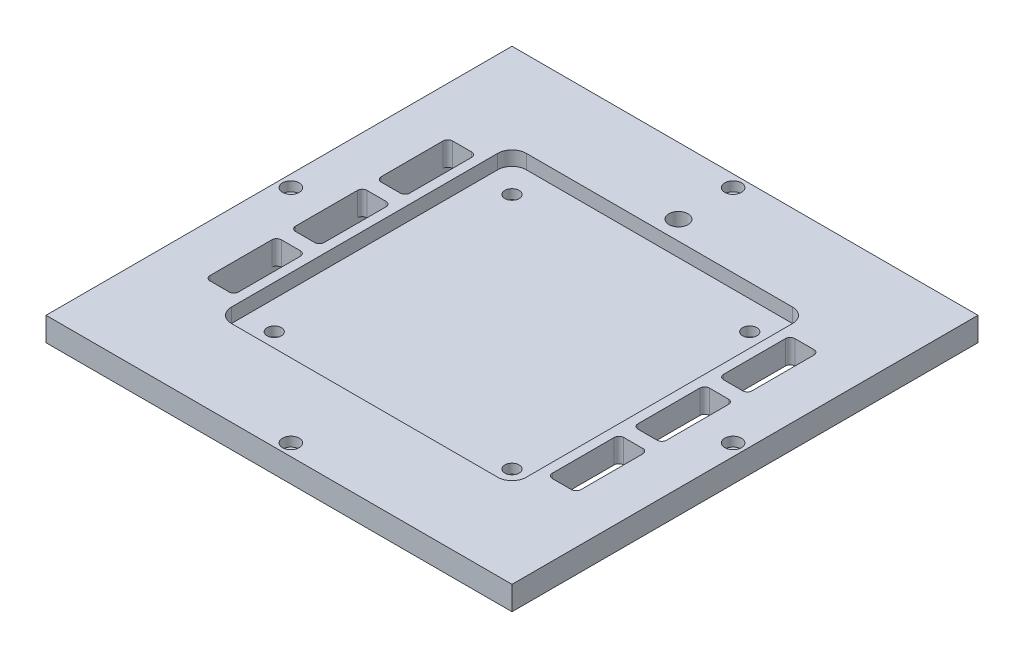
SolidWorks part; units mm, degrees
ref_plane "Front Plane" through (0, 0, 0) normal (0, 0, 1) x (1, 0, 0)
ref_plane "Top Plane" through (0, 0, 0) normal (0, 1, 0) x (1, 0, 0)
ref_plane "Right Plane" through (0, 0, 0) normal (1, 0, 0) x (0, 0, -1)
sketch "Sketch1" plane through (0, 0, 0) normal (0, 1, 0) x (1, 0, 0)
  line L1 (-49, 49) -> (49, 49)
  line L2 (-49, 49) -> (-49, -49)
  line L3 (-49, -49) -> (49, -49)
  line L4 (49, 49) -> (49, -49)
  line L5 (-49, 49) -> (49, -49) construction
  line L6 (-49, -49) -> (49, 49) construction
  point P0 (0, 0)
  dimension "D1" = 98
  dimension "D2" = 98
extrude "Boss-Extrude2" add sketch "Sketch1" along normal blind 5
sketch "Sketch3" plane through (0, 0, 0) normal (0, -1, 0) x (1, 0, 0)
  line L0 (0, 0) -> (0, 3) construction
  line L1 (0, 0) -> (0, -3) construction
  line L2 (0, 0) -> (3, 0) construction
  line L3 (0, 0) -> (-3, 0) construction
  line L4 (0, -3) -> (-3, -3) construction
  line L5 (-3, -3) -> (-3, 3) construction
  line L6 (-3, 3) -> (3, 3) construction
  line L7 (3, 3) -> (3, -3) construction
  line L8 (3, -3) -> (0, -3) construction
  line L9 (3, 0) -> (3, 3)
  line L10 (-16, -3) -> (16, -3) construction
  line L11 (16, -3) -> (16, -40) construction
  line L12 (-16, -3) -> (-16, -40) construction
  line L13 (-16, -40) -> (16, -40) construction
  line L14 (3, 3) -> (3, 40) construction
  line L15 (3, 40) -> (35, 40) construction
  line L16 (35, 40) -> (35, 3) construction
  line L17 (35, 3) -> (3, 3) construction
  line L18 (-35, 3) -> (-3, 3) construction
  line L19 (-35, 40) -> (-35, 3) construction
  line L20 (-3, 40) -> (-35, 40) construction
  line L21 (-3, 3) -> (-3, 40) construction
  line L22 (-30, 6.5) -> (-8, 6.5) construction
  line L24 (-30.8177, 35.1642) -> (-7.1823, 7.8358)
  line L25 (-31.5, 35) -> (-31.5, 8) construction
  line L26 (-30, 36.5) -> (-8, 36.5) construction
  line L27 (-6.5, 35) -> (-6.5, 8) construction
  line L28 (-35, 40) -> (-32.7235, 37.3678)
  line L29 (-35, 3) -> (-32.7235, 5.6322)
  line L30 (-5.2765, 37.3678) -> (-3, 40)
  line L31 (-30.8177, 7.8358) -> (-7.1823, 35.1642)
  line L33 (-5.2765, 5.6322) -> (-3, 3)
  circle A0 centre (-31.5, 36.5) radius 1.5
  circle A1 centre (-6.5, 36.5) radius 1.5
  circle A2 centre (-6.5, 6.5) radius 1.5
  circle A3 centre (-31.5, 6.5) radius 1.5
  circle A4 centre (31.5, 6.5) radius 1.5
  circle A5 centre (6.5, 6.5) radius 1.5
  circle A6 centre (6.5, 36.5) radius 1.5
  circle A7 centre (31.5, 36.5) radius 1.5
  circle A8 centre (12.5, -6.5) radius 1.5
  circle A9 centre (12.5, -36.5) radius 1.5
  circle A10 centre (-12.5, -6.5) radius 1.5
  circle A11 centre (-12.5, -36.5) radius 1.5
sketch "Sketch11" plane through (0, 5, 0) normal (0, 1, 0) x (1, 0, 0)
  line L0 (49, -49) -> (49, 49) construction
  line L1 (-49, 49) -> (49, 49)
  line L2 (-49, 49) -> (-49, -49)
  line L3 (-49, -49) -> (49, -49)
  line L4 (49, 49) -> (49, -49)
  line L5 (-49, -49) -> (49, -49) construction
  line L7 (-46.5, 46.5) -> (46.5, 46.5)
  line L8 (-46.5, 46.5) -> (-46.5, -46.5)
  line L9 (-46.5, -46.5) -> (46.5, -46.5)
  line L10 (46.5, 46.5) -> (46.5, -46.5)
  line L11 (-44, 44) -> (44, 44)
  line L12 (-44, 44) -> (-44, -44)
  line L13 (-44, -44) -> (44, -44)
  line L14 (44, 44) -> (44, -44)
  line L15 (-44, 44) -> (44, -44) construction
  line L16 (-44, -44) -> (44, 44) construction
  point P9 (0, 0)
  point P15 (0, 0)
  dimension "D1" = 93
  dimension "D2" = 93
  dimension "D3" = 88
  dimension "D4" = 88
sketch "Sketch12" plane through (0, 0, 0) normal (0, -1, 0) x (1, 0, 0)
  line L1 (49, -49) -> (-49, -49) construction
  line L2 (49, -49) -> (49, 49) construction
  line L3 (49, 49) -> (-49, 49) construction
  line L4 (-49, -49) -> (-49, 49) construction
  line L5 (-44, 44) -> (44, 44)
  line L6 (-44, 44) -> (-44, -44)
  line L7 (-44, -44) -> (44, -44)
  line L8 (44, 44) -> (44, -44)
  line L9 (-39, 39) -> (39, 39)
  line L10 (-39, 39) -> (-39, -39)
  line L11 (-39, -39) -> (39, -39)
  line L12 (39, 39) -> (39, -39)
  line L13 (-39, 39) -> (39, -39) construction
  line L14 (-39, -39) -> (39, 39) construction
  point P0 (0, 0)
  point P7 (0, 0)
  point P12 (0, 0)
  dimension "D1" = 78
  dimension "D2" = 78
extrude "Boss-Extrude4" add sketch "Sketch12" along normal blind 2 contours L6 L5 L8 L7 | L10 L9 L12 L11
sketch "Sketch13" plane through (0, 5, 0) normal (0, 1, 0) x (1, 0, 0)
  line L0 (49, 0) -> (44, 0)
  line L1 (49, -49) -> (49, 49) construction
  line L2 (0, -49) -> (0, -44)
  line L3 (-49, -49) -> (49, -49) construction
  line L5 (-44, 44) -> (44, 44) construction
  line L6 (-44, 44) -> (-44, -44) construction
  line L7 (-44, -44) -> (44, -44) construction
  line L8 (44, 44) -> (44, -44) construction
  circle A0 centre (46.5, 0) radius 1.75
  circle A1 centre (-46.5, 0) radius 1.75
  circle A2 centre (0, -46.5) radius 1.75
  circle A3 centre (0, 46.5) radius 1.75
  point P9 (0, 0)
  dimension "D1" = 3.5
  dimension "D2" = 3.5
extrude "Cut-Extrude13" cut sketch "Sketch13" against normal blind 2 contours L2 A2 | L2 A2 | A1 | A3 | L0 A0 | L0 A0
sketch "Sketch14" plane through (0, 5, 0) normal (0, 1, 0) x (1, 0, 0)
  circle A0 centre (0, -46.5) radius 1
  circle A1 centre (-46.5, 0) radius 1
  circle A2 centre (46.5, 0) radius 1
  circle A3 centre (0, 46.5) radius 1
extrude "Cut-Extrude14" cut sketch "Sketch14" against normal blind 9
sketch "Sketch16" plane through (0, 5, 0) normal (0, 1, 0) x (1, 0, 0)
  line L1 (-39, 39) -> (39, 39) construction
  line L2 (-39, 39) -> (-39, -39) construction
  line L3 (-39, -39) -> (39, -39) construction
  line L4 (39, 39) -> (39, -39) construction
  line L13 (-31, 31) -> (31, 31)
  line L14 (-31, 31) -> (-31, -31)
  line L15 (-31, -31) -> (31, -31)
  line L16 (31, 31) -> (31, -31)
  line L17 (-31, 31) -> (31, -31) construction
  line L18 (-31, -31) -> (31, 31) construction
  point P0 (0, 0)
  point P6 (0, 0)
  point P7 (0, 0)
  point P11 (0, 0)
  dimension "D1" = 78
  dimension "D2" = 78
  dimension "D3" = 62
  dimension "D4" = 62
extrude "Cut-Extrude15" cut sketch "Sketch16" against normal blind 3
fillet "Fillet1" radius 3 4 edges at (-31, 3.5, 31) (31, 3.5, 31) (31, 3.5, -31) (-31, 3.5, -31)
sketch "Sketch17" plane through (0, 2, 0) normal (0, 1, 0) x (1, 0, 0)
  line L1 (25, 25) -> (-25, 25) construction
  line L2 (25, 25) -> (25, -25) construction
  line L3 (25, -25) -> (-25, -25) construction
  line L4 (-25, 25) -> (-25, -25) construction
  line L5 (25, 25) -> (-25, -25) construction
  line L6 (25, -25) -> (-25, 25) construction
  circle A0 centre (25, 25) radius 1.5
  circle A1 centre (25, -25) radius 1.5
  circle A2 centre (-25, 25) radius 1.5
  circle A3 centre (-25, -25) radius 1.5
  point P0 (0, 0)
  dimension "D1" = 50
  dimension "D2" = 50
extrude "Cut-Extrude16" cut sketch "Sketch17" against normal blind 3
sketch "Sketch21" plane through (0, -2, 0) normal (0, -1, 0) x (1, 0, 0)
  line L0 (-28, -31) -> (-49, -31) construction
  line L1 (-49, -49) -> (-49, 49) construction
  line L2 (-28, 31) -> (-49, 31) construction
  line L3 (-28, 31) -> (28, 31) construction
  line L4 (-36, 7.5) -> (-36, 10.5)
  line L5 (-39, -7.5) -> (-39, 7.5)
  line L6 (-31, 0) -> (-33, 0)
  line L7 (-31, -28) -> (-31, 28) construction
  line L8 (-36, -7.5) -> (-36, -10.5)
  line L9 (-39, -7.5) -> (-33, -7.5)
  line L11 (-39, 7.5) -> (-33, 7.5)
  line L12 (-33, -7.5) -> (-33, 7.5)
  line L13 (-33, 10.5) -> (-33, 25.5)
  line L14 (-39, 25.5) -> (-33, 25.5)
  line L15 (-39, 10.5) -> (-33, 10.5)
  line L16 (-39, 10.5) -> (-39, 25.5)
  line L17 (-39, -10.5) -> (-33, -10.5)
  line L18 (-33, -25.5) -> (-33, -10.5)
  line L19 (-39, -25.5) -> (-39, -10.5)
  line L20 (-39, -25.5) -> (-33, -25.5)
  arc A0 (-28, 31) -> (-31, 28) centre (-28, 28) ccw construction
  point P18 (-39, 0)
  point P23 (0, 0)
  point P27 (-39, 18)
  point P33 (-39, -18)
sketch "Sketch23" plane through (0, 5, 0) normal (0, 1, 0) x (1, 0, 0)
  line L0 (-39, -10.5) -> (-39, -25.5) construction
  line L1 (-39, -25.5) -> (-33, -25.5) construction
  line L2 (-33, -10.5) -> (-33, -25.5) construction
  line L3 (-39, -10.5) -> (-33, -10.5) construction
  line L4 (49, -49) -> (49, 49)
  line L5 (49, 49) -> (-49, 49)
  line L6 (-49, 49) -> (-49, -49)
  line L7 (-49, -49) -> (49, -49)
  line L8 (49, -49) -> (49, 49)
  line L9 (49, 49) -> (-49, 49)
  line L10 (-49, 49) -> (-49, -49)
  line L11 (-49, -49) -> (49, -49)
  line L12 (-39, -7.5) -> (-33, -7.5) construction
  line L13 (-39, 7.5) -> (-39, -7.5) construction
  line L14 (-39, 7.5) -> (-33, 7.5) construction
  line L15 (-33, 7.5) -> (-33, -7.5) construction
  line L16 (-39, 25.5) -> (-39, 10.5) construction
  line L17 (-39, 25.5) -> (-33, 25.5) construction
  line L18 (-39, 10.5) -> (-33, 10.5) construction
  line L19 (-33, 25.5) -> (-33, 10.5) construction
  line L20 (-39, -10.5) -> (-39, -25.5)
  line L21 (-39, -25.5) -> (-33, -25.5)
  line L22 (-33, -10.5) -> (-33, -25.5)
  line L23 (-39, -10.5) -> (-33, -10.5)
  line L24 (-39, -7.5) -> (-33, -7.5)
  line L25 (-39, 7.5) -> (-39, -7.5)
  line L26 (-39, 7.5) -> (-33, 7.5)
  line L27 (-33, 7.5) -> (-33, -7.5)
  line L28 (-39, 25.5) -> (-39, 10.5)
  line L29 (-39, 25.5) -> (-33, 25.5)
  line L30 (-39, 10.5) -> (-33, 10.5)
  line L31 (-33, 25.5) -> (-33, 10.5)
  line L32 (0, 31) -> (0, 25.5)
  line L33 (28, 31) -> (-28, 31) construction
  line L34 (39, -10.5) -> (33, -10.5)
  line L35 (33, -10.5) -> (33, -25.5)
  line L36 (39, -25.5) -> (33, -25.5)
  line L37 (39, -10.5) -> (39, -25.5)
  line L38 (39, 7.5) -> (39, -7.5)
  line L39 (39, 7.5) -> (33, 7.5)
  line L40 (33, 7.5) -> (33, -7.5)
  line L41 (39, -7.5) -> (33, -7.5)
  line L42 (39, 25.5) -> (33, 25.5)
  line L43 (33, 25.5) -> (33, 10.5)
  line L44 (39, 10.5) -> (33, 10.5)
  line L45 (39, 25.5) -> (39, 10.5)
  dimension "D1" = 0
extrude "Cut-Extrude19" cut sketch "Sketch23" against normal blind 12 contours L45 L42 L43 L44 | L41 L38 L39 L40 | L37 L34 L35 L36 | L31 L29 L28 L30 | L27 L26 L25 L24 | L23 L20 L21 L22
fillet "Fillet2" radius 1 24 edges at (-39, 2.5, 10.5) (-33, 2.5, 10.5) (-39, 2.5, 25.5) (-33, 2.5, 25.5) (-39, 2.5, -7.5) (-39, 2.5, 7.5) (-33, 2.5, 7.5) (-33, 2.5, -7.5) (-39, 2.5, -25.5) (-39, 2.5, -10.5) (-33, 2.5, -10.5) (-33, 2.5, -25.5) (33, 2.5, 25.5) (39, 2.5, 25.5) (33, 2.5, 10.5) (39, 2.5, 10.5) (33, 2.5, 7.5) (33, 2.5, -7.5) (39, 2.5, -7.5) (39, 2.5, 7.5) (33, 2.5, -25.5) (33, 2.5, -10.5) (39, 2.5, -10.5) (39, 2.5, -25.5)
sketch "Sketch24" plane through (0, 5, 0) normal (0, 1, 0) x (1, 0, 0)
  line L0 (0, 39) -> (0, 31)
  line L1 (-5.7955, 39) -> (5.7955, 39)
  line L3 (28, 31) -> (-28, 31) construction
  circle A0 centre (0, 35) radius 2
  point P7 (0, 39)
  dimension "D1" = 4
extrude "Cut-Extrude22" cut sketch "Sketch24" against normal blind 12 contours A0
